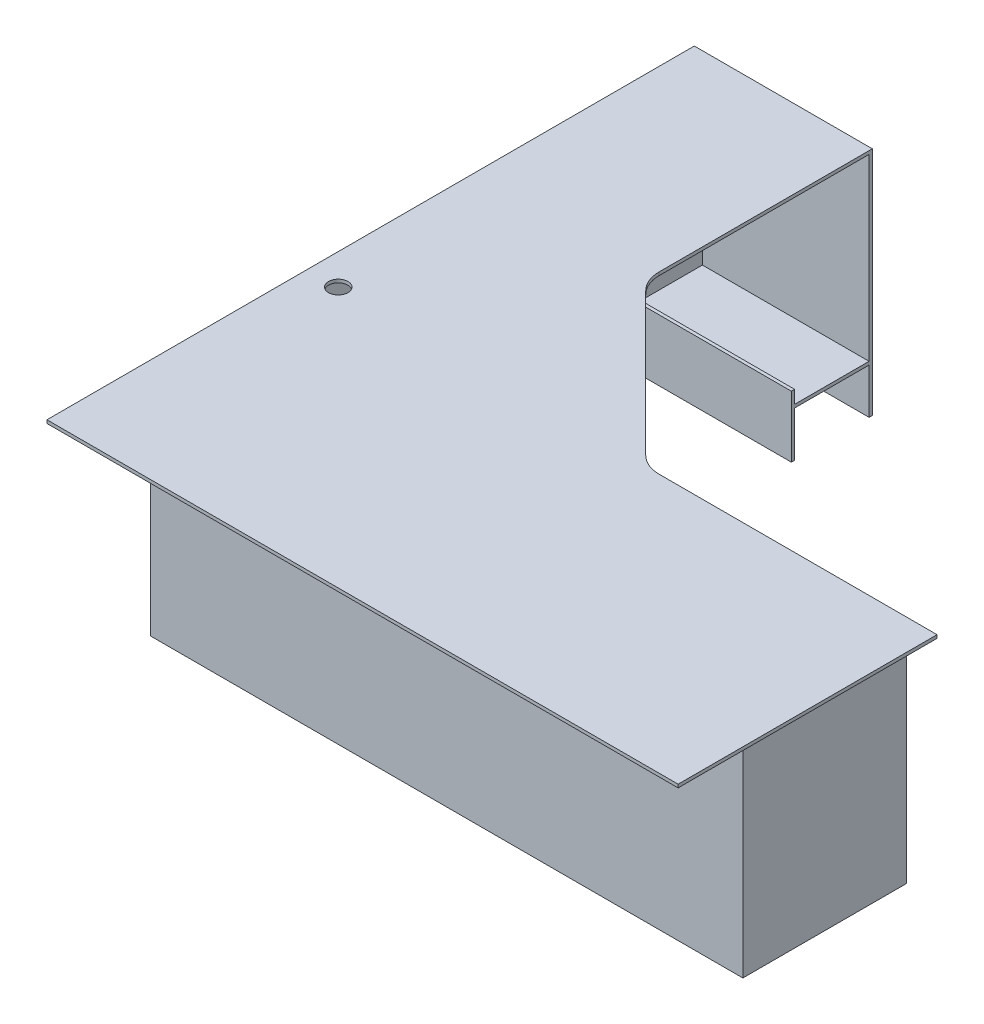
SolidWorks part; units mm, degrees
ref_plane "Alzado" through (0, 0, 0) normal (0, 0, 1) x (1, 0, 0)
ref_plane "Planta" through (0, 0, 0) normal (0, 1, 0) x (1, 0, 0)
ref_plane "Vista lateral" through (0, 0, 0) normal (1, 0, 0) x (0, 0, -1)
sketch "Croquis1" plane through (0, 0, 0) normal (0, 1, 0) x (1, 0, 0)
  line L0 (0, 0) -> (0, 2000)
  line L1 (0, 2000) -> (550, 2000)
  line L2 (550, 2000) -> (550, 1300)
  line L3 (1050, 800) -> (1950, 800)
  line L4 (1950, 800) -> (1950, 0)
  line L5 (1950, 0) -> (0, 0)
  line L6 (550, 1300) -> (1050, 800)
  dimension "D1" = 1400
  dimension "D2" = 550
  dimension "D3" = 800
  dimension "D4" = 2000
  dimension "D5" = 45
  dimension "D6" = 900
extrude "Saliente-Extruir1" add sketch "Croquis1" along normal blind 10
sketch "Croquis2" plane through (0, 0, 0) normal (0, -1, 0) x (1, 0, 0)
  line L0 (25, -295) -> (1855, -295)
  line L1 (1855, -295) -> (1855, -800)
  line L2 (1855, -800) -> (1845, -800)
  line L3 (1950, -800) -> (1050, -800) construction
  line L4 (1845, -800) -> (1845, -305)
  line L5 (1845, -305) -> (35, -305)
  line L6 (35, -305) -> (35, -2000)
  line L7 (550, -2000) -> (0, -2000) construction
  line L8 (35, -2000) -> (25, -2000)
  line L9 (25, -2000) -> (25, -295)
  line L10 (0, 0) -> (1950, 0) construction
  line L11 (0, -2000) -> (0, 0) construction
  line L12 (1950, 0) -> (1950, -800) construction
  dimension "D1" = 10
  dimension "D2" = 10
  dimension "D3" = 10
  dimension "D4" = 295
  dimension "D5" = 25
  dimension "D6" = 95
extrude "Saliente-Extruir2" add sketch "Croquis2" along normal blind 703.6
sketch "Croquis3" plane through (0, 0, 0) normal (0, -1, 0) x (1, 0, 0)
  line L0 (35, -305) -> (1845, -305) construction
  line L1 (35, -2000) -> (35, -305) construction
  circle A0 centre (95, -805) radius 30
  dimension "D1" = 60
  dimension "D2" = 500
  dimension "D3" = 60
extrude "Cortar-Extruir1" cut sketch "Croquis3" against normal through all
fillet "Redondeo1" radius 100 2 edges at (1050, 5, -800) (550, 5, -1300)
sketch "Croquis4" plane through (35, 0, 0) normal (1, 0, 0) x (0, 0, -1)
  line L0 (2000, -703.6) -> (305, -703.6) construction
  line L1 (2000, -703.6) -> (2000, 0) construction
  line L2 (1750, -703.6) -> (1750, -553.6)
  line L3 (1750, -553.6) -> (2000, -553.6)
  line L4 (2000, -553.6) -> (2000, -703.6)
  line L5 (1750, -703.6) -> (1760, -703.6)
  line L6 (1760, -703.6) -> (1760, -563.6)
  line L7 (1760, -563.6) -> (1990, -563.6)
  line L8 (1990, -563.6) -> (1990, -703.6)
  line L9 (1990, -703.6) -> (2000, -703.6)
  dimension "D1" = 10
  dimension "D2" = 10
  dimension "D3" = 10
  dimension "D4" = 150
  dimension "D5" = 250
extrude "Saliente-Extruir3" add sketch "Croquis4" along normal up to vertex (515 mm away) up to point (550, 0, -2000)
sketch "Croquis5" plane through (0, -553.6, 0) normal (0, 1, 0) x (1, 0, 0)
  line L0 (35, 2000) -> (550, 2000)
  line L1 (550, 2000) -> (35, 2000) construction
  line L2 (550, 2000) -> (550, 1750) construction
  line L3 (550, 2000) -> (550, 1990)
  line L4 (550, 1750) -> (35, 1750)
  line L5 (35, 1750) -> (35, 1760)
  line L7 (35, 1760) -> (550, 1760)
  line L8 (550, 1760) -> (550, 1750)
  line L9 (550, 1990) -> (35, 1990)
  line L10 (35, 1990) -> (35, 2000)
  line L13 (35, 2000) -> (35, 1750) construction
  dimension "D1" = 10
  dimension "D2" = 10
extrude "Saliente-Extruir4" add sketch "Croquis5" along normal blind 40
sketch "Croquis6" plane through (0, 0, 0) normal (0, -1, 0) x (1, 0, 0)
  line L0 (1515, -305) -> (1515, -800)
  line L1 (35, -305) -> (1845, -305) construction
  line L2 (1515, -800) -> (1845, -800)
  line L3 (1845, -305) -> (1845, -800) construction
  line L4 (1845, -800) -> (1845, -305)
  line L5 (1845, -305) -> (1515, -305)
  dimension "D2" = 330
extrude "Saliente-Extruir5" add sketch "Croquis6" along normal blind 150 separate body
sketch "Croquis7" plane through (0, 0, -800) normal (0, 0, -1) x (-1, 0, 0)
  line L0 (-1745, -150) -> (-1515, 0) construction
  line L1 (-1515, -150) -> (-1845, -150) construction
  line L2 (-1515, -150) -> (-1515, 0) construction
  line L3 (-1644.6269, -75) -> (-1615.3731, -75) construction
  circle A0 centre (-1630, -75) radius 10
  point P12 (-1630, -75)
  dimension "D1" = 20
extrude "Saliente-Extruir6" add sketch "Croquis7" along normal blind 30 separate body
sketch "Croquis8" plane through (0, -513.6, 0) normal (0, 1, 0) x (1, 0, 0)
  line L0 (550, 2000) -> (35, 2000) construction
  line L1 (35, 1990) -> (550, 1990) construction
  line L2 (550, 1990) -> (550, 2000) construction
  line L4 (550, 2000) -> (35, 2000)
  line L5 (35, 1990) -> (550, 1990)
  line L6 (550, 1990) -> (550, 2000)
  line L7 (35, 2000) -> (35, 1990)
extrude "Saliente-Extruir7" add sketch "Croquis8" along normal up to surface (513.6 mm away) up to face at (95, 0, -835)
